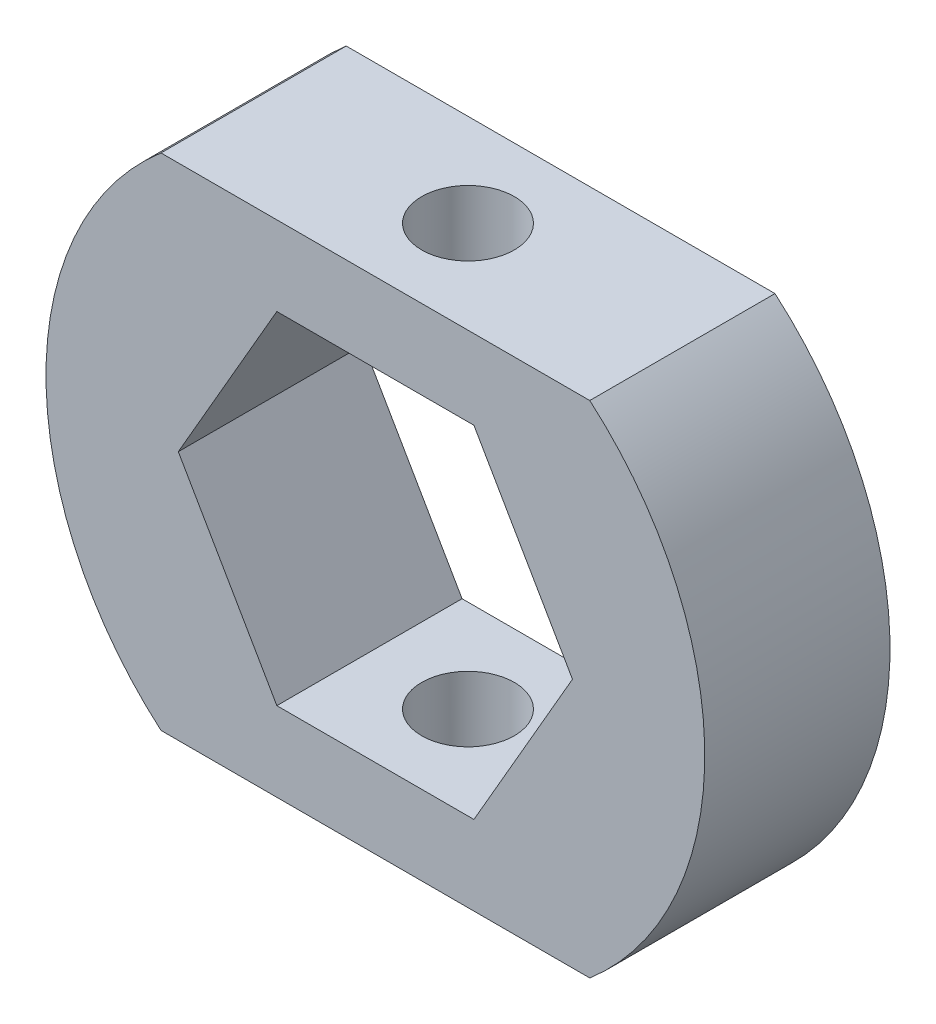
SolidWorks part; units mm, degrees
ref_plane "Front Plane" through (0, 0, 0) normal (0, 0, 1) x (1, 0, 0)
ref_plane "Top Plane" through (0, 0, 0) normal (0, 1, 0) x (1, 0, 0)
ref_plane "Right Plane" through (0, 0, 0) normal (1, 0, 0) x (0, 0, -1)
sketch "Sketch1" plane through (0, 0, 0) normal (0, 0, 1) x (1, 0, 0)
  line L0 (-8.1022, 9.45) -> (8.1022, 9.45)
  line L1 (7.4478, 0) -> (3.7239, 6.45)
  line L2 (3.7239, 6.45) -> (-3.7239, 6.45)
  line L3 (-3.7239, 6.45) -> (-7.4478, 0)
  line L4 (-7.4478, 0) -> (-3.7239, -6.45)
  line L5 (-3.7239, -6.45) -> (3.7239, -6.45)
  line L6 (3.7239, -6.45) -> (7.4478, 0)
  line L7 (8.1022, -9.45) -> (-8.1022, -9.45)
  circle A1 centre (0, 0) radius 6.45 construction
  arc A2 (-8.1022, -9.45) -> (-8.1022, 9.45) centre (0, 0) cw
  arc A3 (8.1022, 9.45) -> (8.1022, -9.45) centre (0, 0) cw
  point P15 (0, -9.45)
  point P16 (-12.4478, 0)
  dimension "D2" = 5
  dimension "D1" = 12.9
  dimension "D3" = 3
extrude "Boss-Extrude1" add sketch "Sketch1" along normal mid plane 7
sketch "Sketch2" plane through (0, 9.45, 0) normal (0, 1, 0) x (1, 0, 0)
  circle A0 centre (0, 0) radius 1.75
  dimension "D1" = 3.5
extrude "Cut-Extrude1" cut sketch "Sketch2" against normal through all
